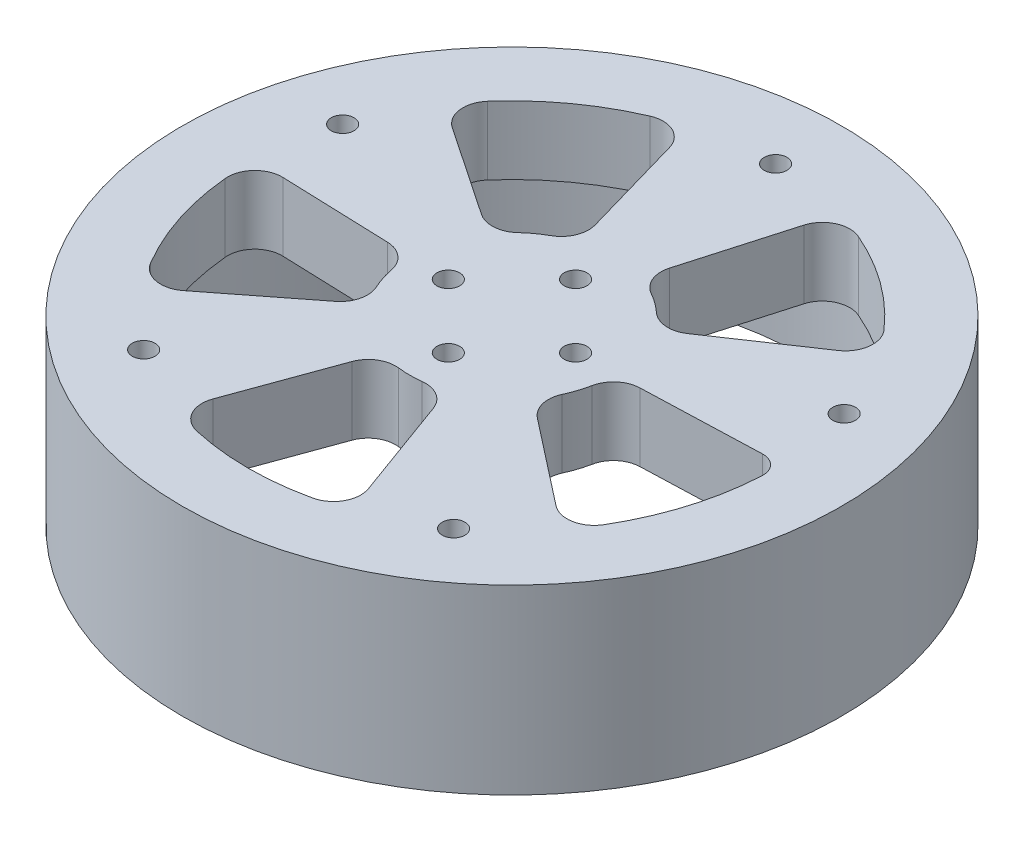
SolidWorks part; units mm, degrees
material "PA Type 6"
ref_plane "Front Plane" through (0, 0, 0) normal (0, 0, 1) x (1, 0, 0)
ref_plane "Top Plane" through (0, 0, 0) normal (0, 1, 0) x (1, 0, 0)
ref_plane "Right Plane" through (0, 0, 0) normal (1, 0, 0) x (0, 0, -1)
sketch "Sketch1" plane through (0, 0, 0) normal (0, 1, 0) x (1, 0, 0)
  circle A0 centre (0, 0) radius 72.5
  circle A1 centre (0, 0) radius 64.5
  dimension "D1" = 145
  dimension "D2" = 8
extrude "Boss-Extrude1" add sketch "Sketch1" along normal mid plane 80
sketch "Sketch4" plane through (0, 0, 0) normal (0, 1, 0) x (1, 0, 0)
  circle A0 centre (0, 0) radius 64.5
  dimension "D1" = 129
extrude "Boss-Extrude3" add sketch "Sketch4" along normal mid plane 30
sketch "Sketch3" plane through (0, 0, 0) normal (0, -1, 0) x (1, 0, 0)
  line L0 (0, 22.5) -> (0, 58) construction
  line L1 (8.9423, 26.2557) -> (17.1001, 48.6689)
  line L2 (-8.9423, 26.2557) -> (-17.1001, 48.6689)
  line L3 (22.2073, 16.6181) -> (41.0027, 31.3027)
  line L4 (27.734, -0.3912) -> (53.793, -1.3012)
  line L5 (22.6672, -15.9851) -> (42.4411, -29.3228)
  line L6 (8.1982, -26.4975) -> (14.7726, -49.4252)
  line L7 (-8.1982, -26.4975) -> (-14.7726, -49.4252)
  line L8 (-22.6672, -15.9851) -> (-42.4411, -29.3228)
  line L9 (-27.734, -0.3912) -> (-51.5711, -1.2236)
  line L10 (-22.2073, 16.6181) -> (-41.0027, 31.3027)
  line L11 (0, 0) -> (-34.0915, 46.923) construction
  circle A1 centre (0, 0) radius 58 construction
  arc A3 (2.6086, 22.3483) -> (-2.6086, 22.3483) centre (0, 0) ccw
  arc A4 (12.7845, 56.5735) -> (-12.7845, 56.5735) centre (0, 0) ccw
  arc A5 (57.9277, 2.8961) -> (49.8539, 29.6409) centre (0, 0) ccw
  arc A6 (22.0606, 4.4251) -> (20.4484, 9.3869) centre (0, 0) ccw
  arc A7 (22.9102, -53.2834) -> (43.5959, -38.2544) centre (0, 0) ccw
  arc A8 (11.0256, -19.6134) -> (15.2464, -16.5469) centre (0, 0) ccw
  arc A9 (-43.5959, -38.2544) -> (-22.9102, -53.2834) centre (0, 0) ccw
  arc A10 (-15.2464, -16.5469) -> (-11.0256, -19.6134) centre (0, 0) ccw
  arc A11 (-49.8539, 29.6409) -> (-57.7552, 5.3234) centre (0, 0) ccw
  arc A12 (-20.4484, 9.3869) -> (-22.0606, 4.4251) centre (0, 0) ccw
  circle A13 centre (-34.0915, 46.923) radius 2.5
  circle A14 centre (34.0915, 46.923) radius 2.5
  circle A15 centre (55.1613, -17.923) radius 2.5
  arc A16 (49.8539, 29.6409) -> (41.0027, 31.3027) centre (44.6966, 26.5746) ccw
  arc A17 (22.2073, 16.6181) -> (20.4484, 9.3869) centre (25.9013, 11.8901) ccw
  arc A18 (22.0606, 4.4251) -> (27.734, -0.3912) centre (27.9434, 5.6051) ccw
  arc A19 (22.6672, -15.9851) -> (15.2464, -16.5469) centre (19.3121, -20.9594) ccw
  arc A20 (43.5959, -38.2544) -> (42.4411, -29.3228) centre (39.086, -34.297) ccw
  arc A21 (22.9102, -53.2834) -> (14.7726, -49.4252) centre (20.5402, -47.7713) cw
  arc A22 (11.0256, -19.6134) -> (8.1982, -26.4975) centre (13.9658, -24.8437) ccw
  arc A23 (-8.1982, -26.4975) -> (-11.0256, -19.6134) centre (-13.9658, -24.8437) ccw
  arc A24 (-22.9102, -53.2834) -> (-14.7726, -49.4252) centre (-20.5402, -47.7713) ccw
  arc A25 (-43.5959, -38.2544) -> (-42.4411, -29.3228) centre (-39.086, -34.297) cw
  arc A26 (-15.2464, -16.5469) -> (-22.6672, -15.9851) centre (-19.3121, -20.9594) ccw
  arc A27 (-27.734, -0.3912) -> (-22.0606, 4.4251) centre (-27.9434, 5.6051) ccw
  arc A28 (-57.7552, 5.3234) -> (-51.5711, -1.2236) centre (-51.7805, 4.7727) ccw
  arc A29 (-49.8539, 29.6409) -> (-41.0027, 31.3027) centre (-44.6966, 26.5746) cw
  arc A30 (-20.4484, 9.3869) -> (-22.2073, 16.6181) centre (-25.9013, 11.8901) ccw
  arc A31 (8.9423, 26.2557) -> (2.6086, 22.3483) centre (3.3042, 28.3078) cw
  arc A32 (-8.9423, 26.2557) -> (-2.6086, 22.3483) centre (-3.3042, 28.3078) ccw
  arc A33 (17.1001, 48.6689) -> (12.7845, 56.5735) centre (11.4619, 50.721) ccw
  arc A34 (-17.1001, 48.6689) -> (-12.7845, 56.5735) centre (-11.4619, 50.721) cw
  arc A35 (57.9277, 2.8961) -> (53.793, -1.3012) centre (53.9326, 2.6963) cw
  circle A36 centre (0, -58) radius 2.5
  circle A37 centre (-55.1613, -17.923) radius 2.5
  point P27 (0, 0)
  point P79 (0, 0)
  dimension "D1" = 20
  dimension "D3" = 5
  dimension "D4" = 58
  dimension "D5" = 6
  dimension "D6" = 4
  dimension "D7" = 22.5
  dimension "D10" = 116
  dimension "D2" = 20
  dimension "D8" = 32
  dimension "D9" = 16
  dimension "D11" = 5
extrude "Cut-Extrude1" cut sketch "Sketch3" against normal mid plane 30
sketch "Sketch6" plane through (0, 15, 0) normal (0, 1, 0) x (1, 0, 0)
  circle A0 centre (0, 0) radius 14 construction
  circle A1 centre (0, 14) radius 2.5
  circle A2 centre (14, 0) radius 2.5
  circle A3 centre (0, -14) radius 2.5
  circle A4 centre (-14, 0) radius 2.5
  point P14 (0, 0)
  dimension "D1" = 4
  dimension "D2" = 28
extrude "Cut-Extrude2" cut sketch "Sketch6" against normal blind 30
sketch "Sketch7" plane through (0, 40, 0) normal (0, 1, 0) x (1, 0, 0)
  circle A0 centre (0, 0) radius 72.5
extrude "Cut-Extrude3" cut sketch "Sketch7" against normal blind 40
